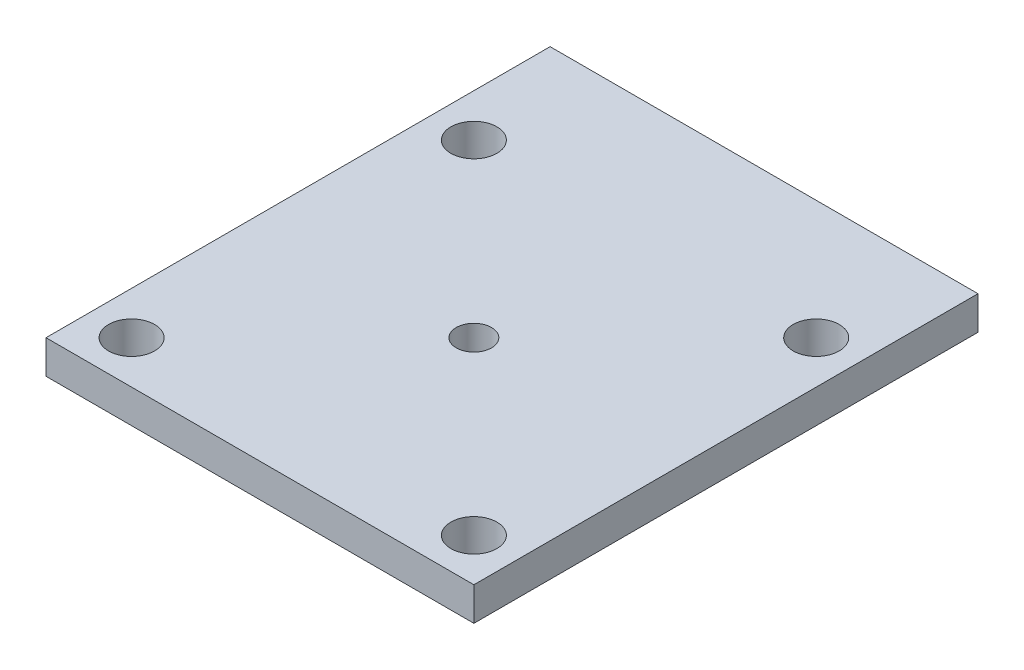
SolidWorks part; units mm, degrees
material "6061 Alloy"
ref_plane "Front Plane" through (0, 0, 0) normal (0, 0, 1) x (1, 0, 0)
ref_plane "Top Plane" through (0, 0, 0) normal (0, 1, 0) x (1, 0, 0)
ref_plane "Right Plane" through (0, 0, 0) normal (1, 0, 0) x (0, 0, -1)
sketch "Sketch1" plane through (0, 0, 0) normal (0, 1, 0) x (1, 0, 0)
  line L1 (-20, -23.5625) -> (20, -23.5625)
  line L2 (-20, -23.5625) -> (-20, 23.5625)
  line L3 (-20, 23.5625) -> (20, 23.5625)
  line L4 (20, -23.5625) -> (20, 23.5625)
  line L5 (-20, -23.5625) -> (20, 23.5625) construction
  line L6 (-20, 23.5625) -> (20, -23.5625) construction
  point P0 (0, 0)
  dimension "D1" = 40
  dimension "D2" = 47.125
extrude "Boss-Extrude1" add sketch "Sketch1" along normal blind 3.125
sketch "Sketch2" plane through (0, 3.125, 0) normal (0, 1, 0) x (1, 0, 0)
  line L0 (-20, -23.5625) -> (20, -23.5625) construction
  line L1 (20, -23.5625) -> (20, 23.5625) construction
  point P0 (16, -19.5625)
  point P8 (-16, -19.5625)
  point P9 (-16, 12.4375)
  point P10 (16, 12.4375)
  dimension "D1" = 4
  dimension "D2" = 4
  dimension "D5" = 32
  dimension "D6" = 32
  dimension "D3" = 2
  dimension "D4" = 2
hole_wizard "M4 Clearance Hole1" positions "Sketch2" profile "Sketch3" hole size "M4" standard "ANSI Metric" end condition through all
sketch "Sketch3" plane through (16, 3.125, 19.5625) normal (1, 0, 0) x (0, 0, 1)
  line L0 (0, 0) -> (0, 3.125)
  line L1 (0, 3.125) -> (2.15, 3.125)
  line L2 (2.15, 3.125) -> (2.15, 0)
  line L5 (2.15, 0) -> (0, 0)
  line L11 (0, -6.35) -> (0, 107.95) construction
  dimension "Thru Hole Dia." = 4.3
  dimension "Thru Hole Depth" = 3.125
sketch "Sketch4" plane through (0, 3.125, 0) normal (0, 1, 0) x (1, 0, 0)
  line L0 (20, -23.5625) -> (20, 23.5625) construction
  line L1 (-20, -23.5625) -> (20, -23.5625) construction
  point P0 (0, -3.5625)
  dimension "D1" = 20
  dimension "D2" = 20
hole_wizard "M4x0.7 Tapped Hole1" positions "Sketch4" profile "Sketch5" tap size "M4x0.7" standard "ANSI Metric" end condition through all
sketch "Sketch5" plane through (0, 3.125, 3.5625) normal (1, 0, 0) x (0, 0, 1)
  line L0 (0, 0) -> (0, 3.125)
  line L1 (0, 3.125) -> (1.65, 3.125)
  line L2 (1.65, 3.125) -> (1.65, 0)
  line L5 (1.65, 0) -> (0, 0)
  line L11 (0, -6.35) -> (0, 107.95) construction
  dimension "Thru Tap Drill Dia." = 3.3
  dimension "Thru Tap Drill Depth" = 3.125
cosmetic thread "Hole Thread1" parameters "D2"=4
